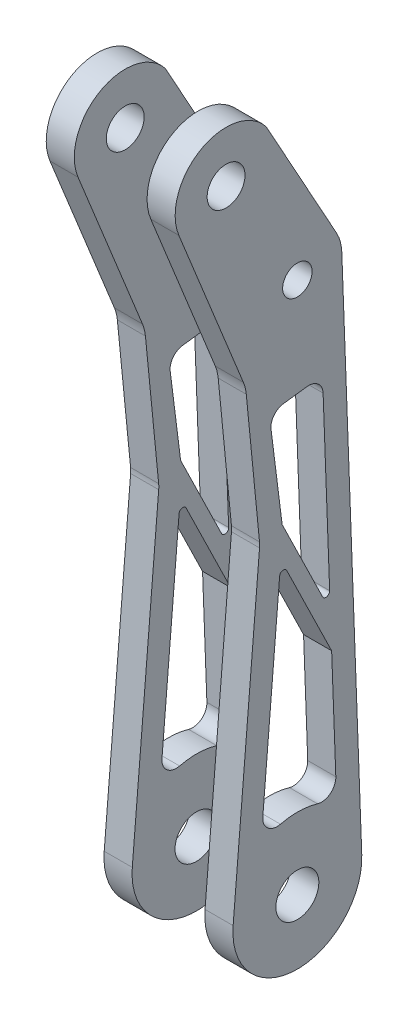
SolidWorks part; units mm, degrees
material "6061-T6 (SS)"
ref_plane "X-Y Datum" through (0, 0, 0) normal (0, 0, 1) x (1, 0, 0)
ref_plane "X-Z Datum" through (0, 0, 0) normal (0, 1, 0) x (1, 0, 0)
ref_plane "Y-Z Datum" through (0, 0, 0) normal (1, 0, 0) x (0, 0, -1)
sketch "Sketch6" plane through (0, 0, 0) normal (1, 0, 0) x (0, 0, -1)
  line L0 (0, 0) -> (0, 95.25) construction
  line L1 (0, 0) -> (0, 118.022) construction
  line L20 (-8.3819, 70.7797) -> (-14.2372, 1.1981)
  line L21 (9.8547, 118.3918) -> (11.5534, 73.1262)
  line L23 (11.5534, 73.1262) -> (14.2775, 0.5358)
  line L24 (-6.91, 150.8965) -> (8.7361, 122.5972)
  line L25 (-26.2646, 139.7057) -> (-11.9697, 104.3659)
  line L26 (-11.3233, 101.7387) -> (-8.39, 71.9341)
  arc A0 (-14.2372, 1.1981) -> (14.2775, 0.5358) centre (0, 0) ccw
  arc A2 (8.7361, 122.5972) -> (9.8547, 118.3918) centre (0, 118.022) cw
  arc A4 (-8.3819, 70.7797) -> (-8.39, 71.9341) centre (-14.7095, 71.3122) ccw
  circle A7 centre (0, 118.022) radius 3.2639
  arc A11 (-26.2646, 139.7057) -> (-6.91, 150.8965) centre (-15.7996, 143.9388) cw
  circle A12 centre (-15.7996, 143.9388) radius 4.1999
  arc A13 (-11.9697, 104.3659) -> (-11.3233, 101.7387) centre (-20.7608, 100.8099) cw
  point P8 (0, 82.55)
  point P12 (0, 82.55)
  point P14 (21.1318, 6.4606)
  point P18 (0, 63.5)
  point P20 (0, 101.6)
  point P25 (11.5534, 73.1262)
  dimension "D2" = 30.3531
  dimension "D7" = 6.35
  dimension "D8" = 69.5816
  dimension "D5" = 32.3365
  dimension "D3" = 6.5278
  dimension "D4" = 8.3998
  dimension "D10" = 72.5904
  dimension "D11" = 173.041
  dimension "D12" = 206.788
  dimension "D1" = 14.2875
  dimension "D13" = 11.2887
  dimension "D19" = 9.4831
  dimension "D6" = 117.856
  dimension "D9" = 4.81
  dimension "D14" = 25.493
  dimension "D15" = 63.5
  dimension "D16" = 82.55
  dimension "D17" = 101.6
  dimension "D18" = 38.1215
  dimension "D20" = 29.9486
extrude "Boss-Extrude3" add sketch "Sketch6" along normal mid plane 28.575
sketch "Sketch7" plane through (14.2875, 0, 0) normal (1, 0, 0) x (0, 0, -1)
  circle A0 centre (0, 0) radius 4.7625
  dimension "D1" = 9.525
extrude "Cut-Extrude1" cut sketch "Sketch7" against normal blind 7.1437 contours A0
sketch "Sketch8" plane through (7.1437, 0, 0) normal (1, 0, 0) x (0, 0, -1)
  circle A0 centre (0, 0) radius 7.9375
  dimension "D1" = 15.875
extrude "Cut-Extrude2" cut sketch "Sketch8" against normal blind 5.5562 contours A0
mirror "Mirror1" about plane through (0, 0, 0) normal (1, 0, 0) of "Cut-Extrude2"
mirror "Mirror2" about plane through (0, 0, 0) normal (1, 0, 0) of "Cut-Extrude1"
fillet "Fillet1" [suppressed] radius 1.5875
ref_plane "Plane1" through (0, 0, 14.2372) normal (0, 0, -1) x (-1, 0, 0)
sketch "Sketch10" plane through (0, 0, 14.2372) normal (0, 0, -1) x (-1, 0, 0)
  line L0 (-8.0645, 155.9765) -> (-8.0645, -18.6485)
  line L2 (-14.2875, 150.8965) -> (14.2875, 150.8965) construction
  line L4 (8.0645, -18.6485) -> (8.0645, 155.9765)
  line L5 (-8.0645, 155.9765) -> (8.0645, 155.9765)
  line L6 (-4.8895, -21.8235) -> (4.8895, -21.8235)
  arc A1 (4.8895, -21.8235) -> (8.0645, -18.6485) centre (4.8895, -18.6485) ccw
  arc A2 (-4.8895, -21.8235) -> (-8.0645, -18.6485) centre (-4.8895, -18.6485) cw
  point P9 (0, 155.9765)
  dimension "D3" = 177.8
  dimension "D1" = 16.129
  dimension "D2" = 5.08
extrude "Cut-Extrude3" cut sketch "Sketch10" along normal mid plane 58.42
sketch "Sketch11" [suppressed] plane through (-12.7, 0, 0) normal (-1, 0, 0) x (0, 0, 1)
  line L0 (-10.7679, 9.3907) -> (-8.2566, 76.313)
  line L1 (10.3203, 9.8805) -> (4.73, 76.313)
  line L2 (7.8475, 77.1297) -> (14.2372, 1.1981) construction
  line L4 (-14.2775, 0.5358) -> (-9.5183, 127.3572) construction
  arc A0 (10.3203, 9.8805) -> (-10.7679, 9.3907) centre (0, 0) ccw
  arc A1 (-8.2566, 76.313) -> (4.73, 76.313) centre (-1.7633, 89.0398) ccw
  dimension "D1" = 28.575
  dimension "D2" = 28.575
  dimension "D3" = 3.175
  dimension "D4" = 3.175
extrude "Cut-Extrude4" [suppressed] cut sketch "Sketch11" against normal blind 4.7625 contours A1 L1 A0 L0
mirror "Mirror3" [suppressed] about plane through (0, 0, 0) normal (1, 0, 0)
sketch "Sketch12" [suppressed] plane through (0, 0, 0) normal (1, 0, 0) x (0, 0, -1)
  line L0 (0, 95.25) -> (0, 120.65) construction
  line L1 (0, 120.65) -> (24.4512, 127.5273) construction
  line L2 (0, 95.25) -> (-24.8767, 90.1209) construction
  line L3 (0, 127) -> (326.3698, 134.0383) construction
  line L4 (0, 95.25) -> (0, 69.85) construction
  dimension "D1" = 50.8
  dimension "D2" = 78.35
  dimension "D3" = 25.4
  dimension "D4" = 25.4
sketch "Sketch13" plane through (14.2875, 0, 0) normal (1, 0, 0) x (0, 0, -1)
  line L0 (-3.3694, 72.7427) -> (-6.2305, 95.423)
  line L2 (-6.2305, 95.423) -> (5.5772, 96.9125)
  line L9 (-3.3198, 70.3537) -> (-8.0907, 13.6586)
  line L10 (5.5772, 96.9125) -> (8.7161, 13.2682)
  line L12 (-8.3819, 70.7797) -> (-14.2372, 1.1981) construction
  line L13 (14.2775, 0.5358) -> (9.8547, 118.3918) construction
  arc A1 (8.7161, 13.2682) -> (-8.0907, 13.6586) centre (0, 0) ccw
  arc A2 (-3.3694, 72.7427) -> (-3.3198, 70.3537) centre (-14.7095, 71.3122) cw
  dimension "D3" = 15.875
  dimension "D4" = 11.43
  dimension "D2" = 22.86
  dimension "D5" = 12
  dimension "D6" = 5.08
  dimension "D7" = 5.08
  dimension "D1" = 11.9013
extrude "Cut-Extrude5" cut sketch "Sketch13" against normal blind 28.575 contours L2 L10 A1 L9 A2 L0
fillet "Fillet2" radius 3.175 4 edges at (-11.176, 95.423, 6.2305) (-11.176, 96.9125, -5.5772) (-11.176, 13.2682, -8.7161) (-11.176, 13.6586, 8.0907)
fillet "Fillet3" radius 3.175 4 edges at (11.176, 95.423, 6.2305) (11.176, 13.2682, -8.7161) (11.176, 13.6586, 8.0907) (11.176, 96.9125, -5.5772)
sketch "Sketch21" plane through (14.2875, 0, 0) normal (1, 0, 0) x (0, 0, -1)
  line L0 (-3.3694, 72.7427) -> (7.3045, 50.8849)
  line L1 (5.7072, 93.4476) -> (8.5234, 18.4022) construction
  line L2 (-3.6749, 66.1329) -> (7.5986, 43.047)
  line L3 (-3.3198, 70.3537) -> (-7.6599, 18.7781) construction
  line L4 (7.5986, 43.047) -> (7.3045, 50.8849)
  line L5 (-3.6749, 66.1329) -> (-3.3198, 70.3537)
  arc A0 (-3.3198, 70.3537) -> (-3.3694, 72.7427) centre (-14.7095, 71.3122) ccw
  dimension "D1" = 3.175
  dimension "D2" = 210.838
extrude "Boss-Extrude4" add sketch "Sketch21" against normal up to surface (6.223 mm away) up to face at (8.0645, 58.8813, 0.6223)
fillet "Fillet4" radius 0.8255 2 edges at (11.176, 66.1329, 3.6749) (11.176, 50.8849, -7.3045)
sketch "Sketch23" plane through (-14.2875, 0, -12.7) normal (1, 0, 0) x (0, 0, -1)
  line L0 (-16.3614, 74.2421) -> (-5.4322, 51.8613)
  line L2 (-16.3102, 66.9017) -> (-5.1381, 44.0234)
  line L4 (-5.1381, 44.0234) -> (-5.4322, 51.8613)
  line L5 (-16.3102, 66.9017) -> (-16.0198, 70.3537)
  line L6 (-6.9928, 93.4476) -> (-4.1766, 18.4022) construction
  arc A0 (-16.0198, 70.3537) -> (-16.3614, 74.2421) centre (-27.4095, 71.3122) ccw
  arc A1 (-16.0198, 70.3537) -> (-16.0694, 72.7427) centre (-27.4095, 71.3122) ccw construction
  dimension "D1" = 3.175
  dimension "D2" = 210.838
extrude "Boss-Extrude5" add sketch "Sketch23" along normal up to surface (6.223 mm away) up to face at (-8.0645, 58.8813, 0.6223)
fillet "Fillet6" radius 0.8255 2 edges at (-11.176, 51.8613, -7.2678) (-11.176, 66.9017, 3.6102)
ref_plane "Plane2" through (26.9875, 0, 0) normal (1, 0, 0) x (0, 0, -1)
sketch "Sketch17" plane through (-14.2875, 0, 0) normal (-1, 0, 0) x (0, 0, 1)
  line L1 (-15.7464, -15.0456) -> (16.41, -15.0456)
  line L2 (-15.7464, -15.0456) -> (-15.7464, 137.8624)
  line L3 (-15.7464, 137.8624) -> (16.41, 137.8624)
  line L4 (16.41, -15.0456) -> (16.41, 137.8624)
  arc A0 (-14.2775, 0.5358) -> (14.2372, 1.1981) centre (0, 0) ccw construction
  point P8 (0.3318, -14.2836)
  point P9 (0.3318, -15.0456)
  dimension "D1" = 152.908
  dimension "D2" = 32.1564
  dimension "D3" = 0.762
sketch "Sketch18" plane through (26.9875, 0, 0) normal (1, 0, 0) x (0, 0, -1)
  point P0 (0, 0)
sketch3d "3DSketch1"
  line L0 (14.2875, 0, 0) -> (-14.2875, 0, 0) construction
  line L1 (8.0645, 0, 0) -> (14.2875, 0, 0) construction
  line L2 (14.2875, 0, 0) -> (8.0645, 0, 0) construction
  line L4 (-8.0645, 0, 0) -> (-14.2875, 0, 0) construction
  point P10 (0, 0, 0)
sketch3d "3DSketch2"
  line L0 (14.2875, 143.9388, 15.7996) -> (-14.2875, 143.9388, 15.7996) construction
  line L3 (14.2875, 118.022, 0) -> (-14.2875, 118.022, 0) construction
  line L4 (14.2875, 118.022, 0) -> (8.0645, 118.022, 0) construction
  line L5 (-8.0645, 118.022, 0) -> (-14.2875, 118.022, 0) construction
  circle A0 centre (-14.2875, 143.9388, 15.7996) radius 4.1999 construction
  point P5 (-10.0876, 143.9388, 15.7996)
  point P6 (0, 143.9388, 15.7996)
  point P13 (0, 118.022, 0)
sketch "Sketch19" plane through (0, 0, 0) normal (0, 0, 1) x (1, 0, 0)
  line L0 (0, 0) -> (0, -38.1) construction
  dimension "D1" = 38.1
